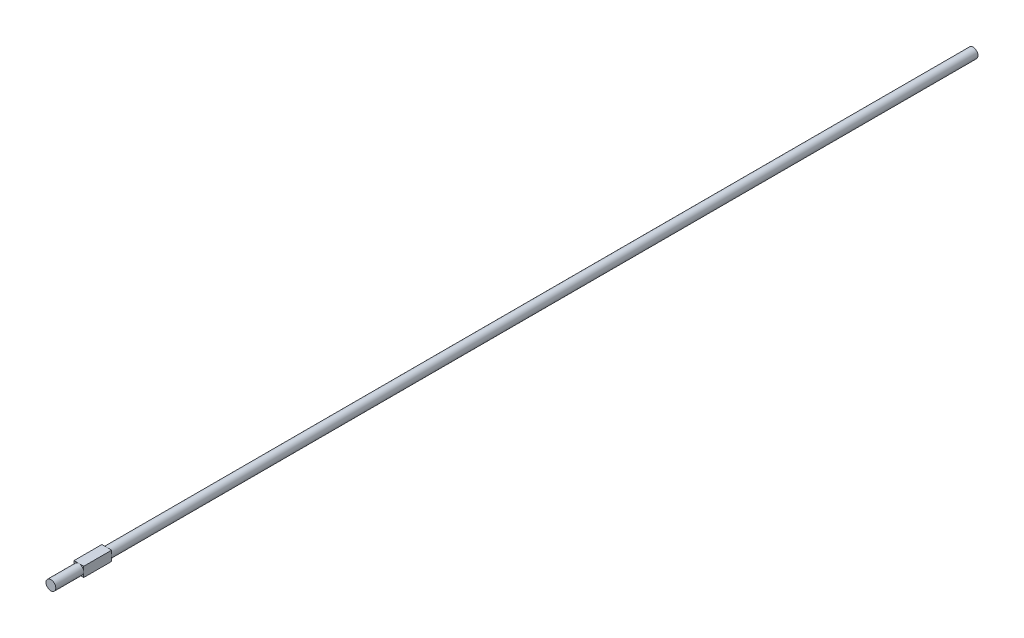
SolidWorks part; units mm, degrees
ref_plane "정면" through (0, 0, 0) normal (0, 0, 1) x (1, 0, 0)
ref_plane "윗면" through (0, 0, 0) normal (0, 1, 0) x (1, 0, 0)
ref_plane "우측면" through (0, 0, 0) normal (1, 0, 0) x (0, 0, -1)
sketch "스케치1" plane through (0, 0, 0) normal (0, 0, 1) x (1, 0, 0)
  circle A0 centre (0, 0) radius 3.5
  dimension "D1" = 7
extrude "보스-돌출1" add sketch "스케치1" along normal blind 660
sketch "스케치2" plane through (0, 0, 0) normal (0, 0, -1) x (-1, 0, 0)
  text T0 "top" font "Century Gothic" height in points 9
extrude "컷-돌출1" cut sketch "스케치2" against normal blind 0.04
ref_plane "평면1" through (0, 0, 620) normal (0, 0, 1) x (1, 0, 0)
sketch "스케치4" plane through (0, 0, 620) normal (0, 0, 1) x (1, 0, 0)
  line L1 (-3.5, 3.5) -> (3.5, 3.5)
  line L2 (-3.5, 3.5) -> (-3.5, -3.5)
  line L3 (-3.5, -3.5) -> (3.5, -3.5)
  line L4 (3.5, 3.5) -> (3.5, -3.5)
  line L5 (-3.5, 3.5) -> (3.5, -3.5) construction
  line L6 (-3.5, -3.5) -> (3.5, 3.5) construction
  point P0 (0, 0)
  dimension "D1" = 7
  dimension "D2" = 7
extrude "보스-돌출2" add sketch "스케치4" along normal blind 20
